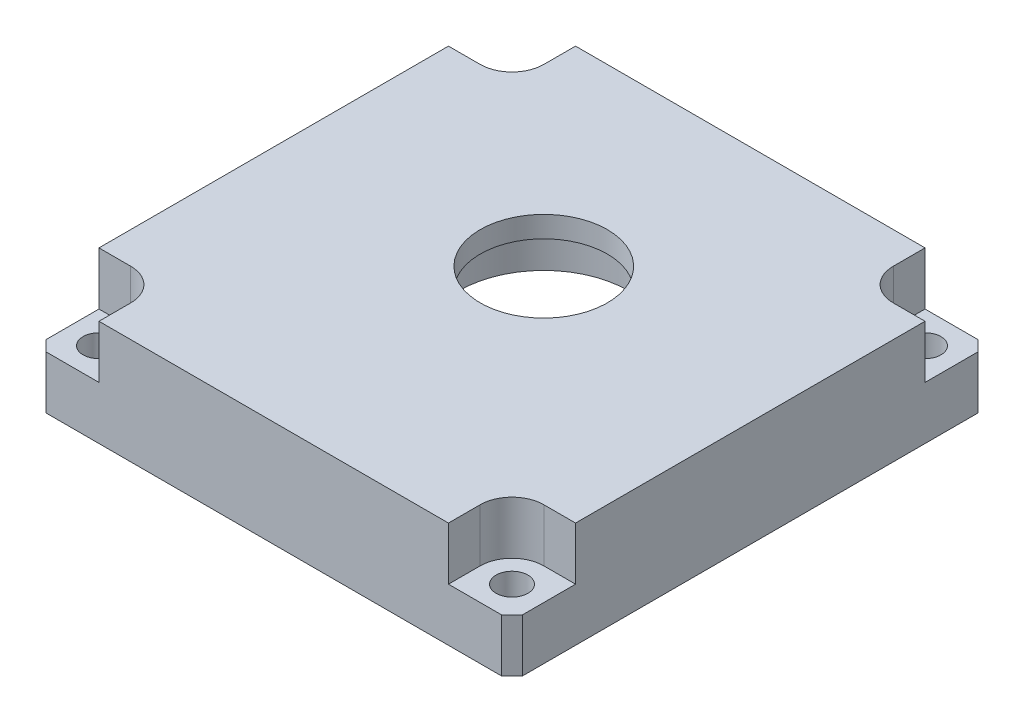
SolidWorks part; units mm, degrees
ref_plane "前视基准面" through (0, 0, 0) normal (0, 0, 1) x (1, 0, 0)
ref_plane "上视基准面" through (0, 0, 0) normal (0, 1, 0) x (1, 0, 0)
ref_plane "右视基准面" through (0, 0, 0) normal (1, 0, 0) x (0, 0, -1)
sketch "草图1" plane through (0, 0, 0) normal (0, 1, 0) x (1, 0, 0)
  line L1 (-22.5, -22.5) -> (22.5, -22.5)
  line L2 (-22.5, -22.5) -> (-22.5, 22.5)
  line L3 (-22.5, 22.5) -> (22.5, 22.5)
  line L4 (22.5, -22.5) -> (22.5, 22.5)
  line L5 (-22.5, -22.5) -> (22.5, 22.5) construction
  line L6 (-22.5, 22.5) -> (22.5, -22.5) construction
  point P0 (0, 0)
  dimension "D1" = 45
  dimension "D2" = 45
extrude "凸台-拉伸1" add sketch "草图1" along normal blind 10
sketch "草图2" plane through (0, 0, 0) normal (0, 1, 0) x (1, 0, 0)
  line L0 (0, 0) -> (0, 3) construction
  circle A0 centre (0, 3) radius 4
  dimension "D1" = 8
  dimension "D2" = 3
extrude "切除-拉伸4" cut sketch "草图2" along normal through all contours A0
sketch "草图3" plane through (0, 0, 0) normal (0, -1, 0) x (1, 0, 0)
  circle A0 centre (0, -3) radius 15
  dimension "D1" = 30
extrude "切除-拉伸5" cut sketch "草图3" against normal blind 4
sketch "草图4" plane through (0, 4, 0) normal (0, -1, 0) x (1, 0, 0)
  circle A0 centre (0, -3) radius 8
  dimension "D1" = 16
extrude "切除-拉伸6" cut sketch "草图4" against normal blind 4
sketch "草图5" plane through (0, 10, 0) normal (0, 1, 0) x (1, 0, 0)
  line L0 (0, 22.5) -> (0, -22.5) construction
  line L1 (22.5, 22.5) -> (-22.5, 22.5) construction
  line L2 (-22.5, -22.5) -> (22.5, -22.5) construction
  line L3 (-22.5, 0) -> (22.5, 0) construction
  line L4 (-22.5, 22.5) -> (-22.5, -22.5) construction
  line L5 (22.5, -22.5) -> (22.5, 22.5) construction
  circle A0 centre (-19.5, 19.5) radius 1.5
  circle A1 centre (19.5, 19.5) radius 1.5
  circle A2 centre (19.5, -19.5) radius 1.5
  circle A3 centre (-19.5, -19.5) radius 1.5
  dimension "D1" = 3
  dimension "D2" = 3
  dimension "D3" = 3
extrude "切除-拉伸7" cut sketch "草图5" against normal through all
sketch "草图6" plane through (0, 10, 0) normal (0, 1, 0) x (1, 0, 0)
  line L0 (0, 22.5) -> (0, -22.5) construction
  line L1 (22.5, 22.5) -> (-22.5, 22.5) construction
  line L2 (-22.5, -22.5) -> (22.5, -22.5) construction
  line L3 (-22.5, 0) -> (22.5, 0) construction
  line L4 (-22.5, 22.5) -> (-22.5, -22.5) construction
  line L5 (22.5, -22.5) -> (22.5, 22.5) construction
  line L6 (-16.5, 22.5) -> (-16.5, 19.5)
  line L7 (-19.5, 16.5) -> (-22.5, 16.5)
  line L8 (-22.5, 16.5) -> (-22.5, 22.5)
  line L9 (-22.5, 22.5) -> (-16.5, 22.5)
  line L10 (22.5, 16.5) -> (22.5, 22.5)
  line L11 (19.5, 16.5) -> (22.5, 16.5)
  line L12 (16.5, 22.5) -> (16.5, 19.5)
  line L13 (22.5, 22.5) -> (16.5, 22.5)
  line L14 (19.5, -16.5) -> (22.5, -16.5)
  line L15 (16.5, -22.5) -> (16.5, -19.5)
  line L16 (22.5, -22.5) -> (16.5, -22.5)
  line L17 (22.5, -16.5) -> (22.5, -22.5)
  line L18 (-22.5, -16.5) -> (-22.5, -22.5)
  line L19 (-19.5, -16.5) -> (-22.5, -16.5)
  line L20 (-16.5, -22.5) -> (-16.5, -19.5)
  line L21 (-22.5, -22.5) -> (-16.5, -22.5)
  arc A0 (-16.5, 19.5) -> (-19.5, 16.5) centre (-19.5, 19.5) cw
  arc A1 (16.5, 19.5) -> (19.5, 16.5) centre (19.5, 19.5) ccw
  arc A2 (16.5, -19.5) -> (19.5, -16.5) centre (19.5, -19.5) cw
  arc A3 (-16.5, -19.5) -> (-19.5, -16.5) centre (-19.5, -19.5) ccw
  dimension "D1" = 3
extrude "切除-拉伸8" cut sketch "草图6" against normal blind 5
chamfer "倒角1" distance 1 angle 45 4 edges at (22.5, 2.5, 22.5) (-22.5, 2.5, 22.5) (22.5, 2.5, -22.5) (-22.5, 2.5, -22.5)
sketch "草图7" plane through (0, 8, 0) normal (0, -1, 0) x (1, 0, 0)
  circle A0 centre (0, -3) radius 6
  dimension "D1" = 12
extrude "切除-拉伸9" cut sketch "草图7" against normal through all
